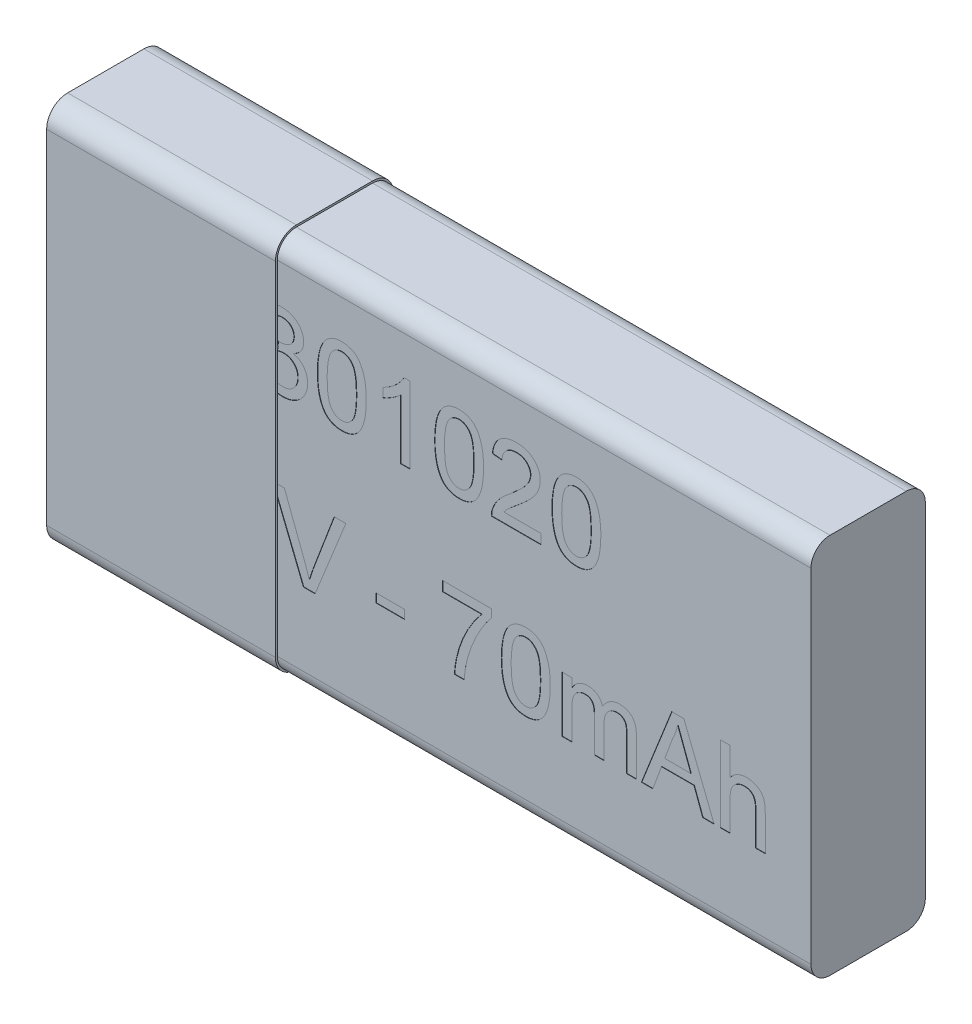
SolidWorks part; units mm, degrees
ref_plane "Plan de face" through (0, 0, 0) normal (0, 0, 1) x (1, 0, 0)
ref_plane "Plan de dessus" through (0, 0, 0) normal (0, 1, 0) x (1, 0, 0)
ref_plane "Plan de droite" through (0, 0, 0) normal (1, 0, 0) x (0, 0, -1)
sketch "Sketch1" plane through (0, 0, 0) normal (0, 0, 1) x (1, 0, 0)
  line L1 (10, -5) -> (-10, -5)
  line L2 (10, -5) -> (10, 5)
  line L3 (10, 5) -> (-10, 5)
  line L4 (-10, -5) -> (-10, 5)
  line L5 (10, -5) -> (-10, 5) construction
  line L6 (10, 5) -> (-10, -5) construction
  point P0 (0, 0)
  dimension "D1" = 10
  dimension "D2" = 20
extrude "Boss-Extrude1" add sketch "Sketch1" along normal blind 3
fillet "Fillet1" radius 0.5 4 edges at (0, -5, 0) (0, -5, 3) (0, 5, 3) (0, 5, 0)
sketch "Sketch2" plane through (-10, 0, 0) normal (-1, 0, 0) x (0, 0, 1)
  line L4 (0, 4.5) -> (0, -4.5) construction
  line L5 (2.5, -5) -> (0.5, -5) construction
  line L6 (3, 4.5) -> (3, -4.5) construction
  line L7 (2.5, 5) -> (0.5, 5) construction
  line L8 (0.5, -5.05) -> (2.5, -5.05)
  line L9 (-0.05, 4.5) -> (-0.05, -4.5)
  line L10 (2.5, 5.05) -> (0.5, 5.05)
  line L11 (3.05, -4.5) -> (3.05, 4.5)
  line L12 (0.5, -5.05) -> (2.5, -5.05)
  line L13 (-0.05, 4.5) -> (-0.05, -4.5)
  line L14 (2.5, 5.05) -> (0.5, 5.05)
  line L15 (3.05, -4.5) -> (3.05, 4.5)
  line L16 (0, 4.5) -> (0, -4.5)
  line L17 (2.5, -5) -> (0.5, -5)
  line L18 (3, 4.5) -> (3, -4.5)
  line L19 (2.5, 5) -> (0.5, 5)
  arc A4 (0.5, 5) -> (0, 4.5) centre (0.5, 4.5) ccw construction
  arc A5 (0, -4.5) -> (0.5, -5) centre (0.5, -4.5) ccw construction
  arc A6 (2.5, -5) -> (3, -4.5) centre (2.5, -4.5) ccw construction
  arc A7 (3, 4.5) -> (2.5, 5) centre (2.5, 4.5) ccw construction
  arc A8 (2.5, -5.05) -> (3.05, -4.5) centre (2.5, -4.5) ccw
  arc A9 (-0.05, -4.5) -> (0.5, -5.05) centre (0.5, -4.5) ccw
  arc A10 (0.5, 5.05) -> (-0.05, 4.5) centre (0.5, 4.5) ccw
  arc A11 (3.05, 4.5) -> (2.5, 5.05) centre (2.5, 4.5) ccw
  arc A12 (2.5, -5.05) -> (3.05, -4.5) centre (2.5, -4.5) ccw
  arc A13 (-0.05, -4.5) -> (0.5, -5.05) centre (0.5, -4.5) ccw
  arc A14 (0.5, 5.05) -> (-0.05, 4.5) centre (0.5, 4.5) ccw
  arc A15 (3.05, 4.5) -> (2.5, 5.05) centre (2.5, 4.5) ccw
  arc A16 (0.5, 5) -> (0, 4.5) centre (0.5, 4.5) ccw
  arc A17 (0, -4.5) -> (0.5, -5) centre (0.5, -4.5) ccw
  arc A18 (2.5, -5) -> (3, -4.5) centre (2.5, -4.5) ccw
  arc A19 (3, 4.5) -> (2.5, 5) centre (2.5, 4.5) ccw
  dimension "D1" = 0.05
extrude "Boss-Extrude2" add sketch "Sketch2" against normal blind 6 separate body
sketch "Sketch5" plane through (0, 0, 3) normal (0, 0, 1) x (1, 0, 0)
  line L1 (-7.9429, -2.5072) -> (7.9429, -2.5072) construction
  line L2 (-7.9429, -2.5072) -> (-7.9429, 1.4928) construction
  line L3 (-7.9429, 1.4928) -> (7.9429, 1.4928) construction
  line L4 (7.9429, -2.5072) -> (7.9429, 1.4928) construction
  line L5 (-7.9429, -2.5072) -> (7.9429, 1.4928) construction
  line L6 (-7.9429, 1.4928) -> (7.9429, -2.5072) construction
  text T0 "301020\r\n3.7V - 70mAh" font "Arial" height 2
  point P8 (0, -0.5072)
  dimension "D1" = 4
extrude "Cut-Extrude1" cut sketch "Sketch5" against normal blind 0.01
